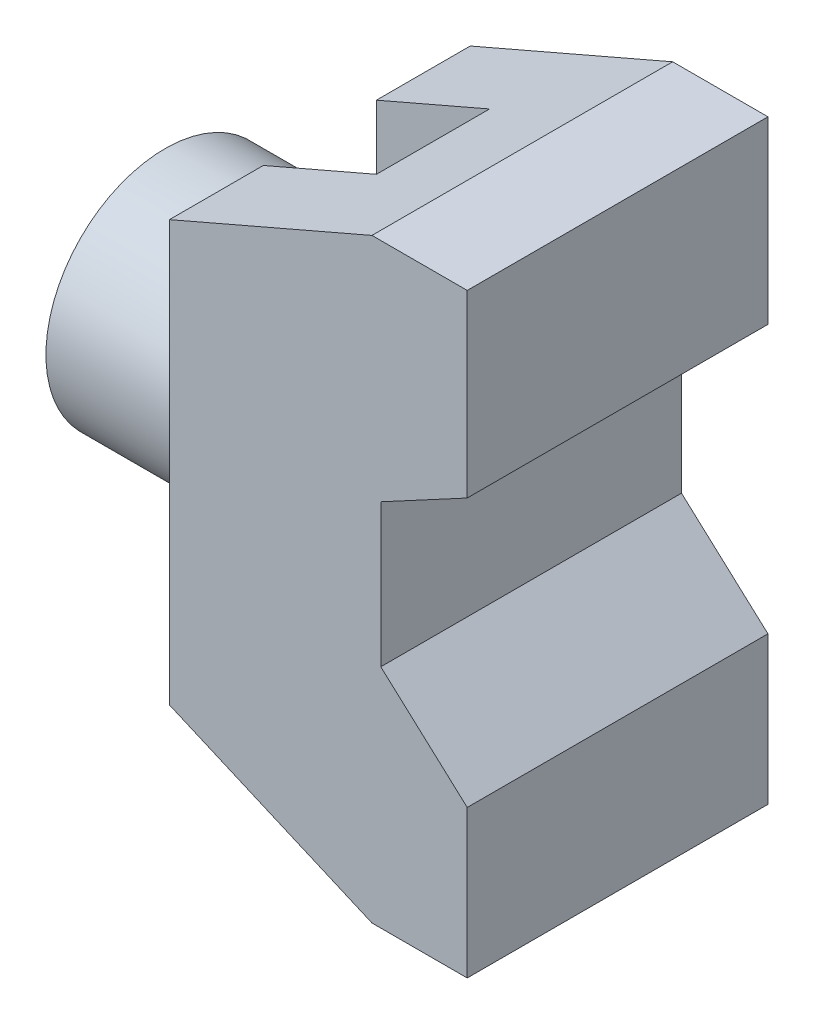
SolidWorks part; units mm, degrees
ref_plane "Front Plane" through (0, 0, 0) normal (0, 0, 1) x (1, 0, 0)
ref_plane "Top Plane" through (0, 0, 0) normal (0, 1, 0) x (1, 0, 0)
ref_plane "Right Plane" through (0, 0, 0) normal (1, 0, 0) x (0, 0, -1)
sketch "Sketch2" plane through (0, 0, 0) normal (1, 0, 0) x (0, 0, -1)
  circle A0 centre (0, 0) radius 10
  circle A1 centre (0, 0) radius 20
  dimension "D1" = 40
  dimension "D2" = 20
extrude "Boss-Extrude1" add sketch "Sketch2" along normal blind 26
sketch "Sketch3" plane through (26, 0, 0) normal (1, 0, 0) x (0, 0, -1)
  line L1 (-25.25, 50) -> (25.25, 50)
  line L2 (-25.25, 50) -> (-25.25, -50)
  line L3 (-25.25, -50) -> (25.25, -50)
  line L4 (25.25, 50) -> (25.25, -50)
  line L5 (-25.25, 50) -> (25.25, -50) construction
  line L6 (-25.25, -50) -> (25.25, 50) construction
  point P0 (0, 0)
  dimension "D1" = 50.5
  dimension "D2" = 100
extrude "Boss-Extrude2" add sketch "Sketch3" along normal blind 50
sketch "Sketch6" plane through (0, -50, 0) normal (0, -1, 0) x (1, 0, 0)
  line L0 (0, 0) -> (76, 0) construction
  line L1 (76, 25.25) -> (76, -25.25) construction
  line L2 (26, 20) -> (26, -20) construction
  line L3 (26, 9.5) -> (45, 9.5)
  line L4 (26, 9.5) -> (26, -9.5)
  line L5 (26, -9.5) -> (45, -9.5)
  line L6 (45, 9.5) -> (45, -9.5)
  dimension "D1" = 19
  dimension "D2" = 19
extrude "Cut-Extrude1" cut sketch "Sketch6" against normal through all
sketch "Sketch7" plane through (0, 0, -25.25) normal (0, 0, -1) x (-1, 0, 0)
  line L6 (0, 0) -> (-86.8992, 0) construction
  line L8 (-76, 50) -> (-26, 50) construction
  line L10 (-60, 50) -> (-26, 50)
  line L11 (-26, 50) -> (-26, 35.2949)
  line L12 (-60, 50) -> (-26, 35.2949)
  line L13 (-60, -50) -> (-26, -35.2949)
  line L14 (-26, -50) -> (-26, -35.2949)
  line L15 (-60, -50) -> (-26, -50)
  line L16 (-26, -50) -> (-26, 50) construction
  point P3 (-26, 0.2949)
  dimension "D1" = 34
  dimension "D2" = 49.7051
  dimension "D3" = 14.7051
extrude "Cut-Extrude5" cut sketch "Sketch7" against normal through all contours L10 L11 L12 | L13 L14 L15
sketch "Sketch9" plane through (0, 0, -25.25) normal (0, 0, -1) x (-1, 0, 0)
  line L0 (0, 0) -> (-86.7506, 0) construction
  line L1 (-76, 19.8072) -> (-76, -25.1928)
  line L2 (-76, -50) -> (-76, 50) construction
  line L3 (-61.4835, 12) -> (-61.4835, -12)
  line L4 (-61.4835, 12) -> (-76, 19.8072)
  line L5 (-61.4835, -12) -> (-76, -25.1928)
  line L6 (-26, -35.2949) -> (-26, 35.2949) construction
  line L7 (-76, 50) -> (-60, 50) construction
  point P8 (-76, -2.6928)
  point P11 (-61.4835, 0)
  dimension "D1" = 45
  dimension "D2" = 24
  dimension "D3" = 35.4835
  dimension "D4" = 30.1928
extrude "Cut-Extrude6" cut sketch "Sketch9" against normal through all
